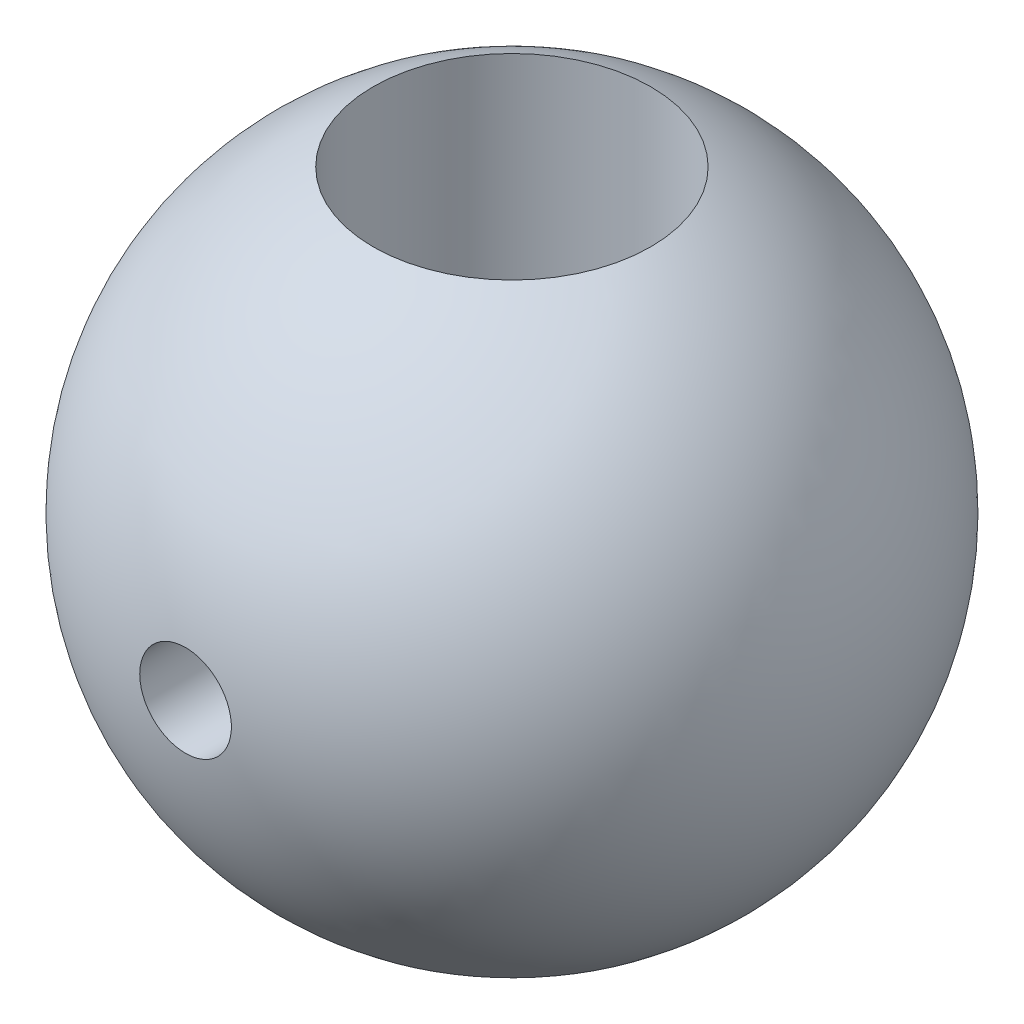
SolidWorks part; units mm, degrees
material "1.4028 (X30Cr13)"
ref_plane "Alzado" through (0, 0, 0) normal (0, 0, 1) x (1, 0, 0)
ref_plane "Planta" through (0, 0, 0) normal (0, 1, 0) x (1, 0, 0)
ref_plane "Vista lateral" through (0, 0, 0) normal (1, 0, 0) x (0, 0, -1)
sketch "Croquis1" plane through (0, 0, 0) normal (0, 0, 1) x (1, 0, 0)
  line L0 (0, -9.5) -> (0, 9.5)
  arc A1 (0, 9.5) -> (0, -9.5) centre (0, 0) cw
  point P2 (0, 0)
  point P4 (0, 0)
  point P5 (0, 0)
  point P8 (0, 0)
  point P9 (0, 0)
  point P10 (0, 0)
  dimension "D1" = 19
revolve "Revolución1" add sketch "Croquis1" angle 360 about L0
sketch "Croquis2" plane through (0, 0, 0) normal (0, 1, 0) x (1, 0, 0)
  circle A0 centre (0, 0) radius 4
  dimension "D1" = 8
extrude "Cortar-Extruir1" cut sketch "Croquis2" against normal blind 10 and the other way through all
hole_wizard "Diámetro de taladro #37 (0.104)1" positions "Croquis3" profile "Croquis4" hole size "#37" standard "Progressive"
sketch "Croquis3" plane through (0, 0, 0) normal (0, 0, 1) x (1, 0, 0)
  point P0 (0, 0)
sketch "Croquis4" plane through (0, 0, 0) normal (1, 0, 0) x (0, 1, 0)
  line L0 (0, 0) -> (0, 9.5)
  line L1 (0, 9.5) -> (1.3208, 9.5)
  line L2 (1.3208, 9.5) -> (1.3208, 0)
  line L5 (1.3208, 0) -> (0, 0)
  line L11 (0, -6.35) -> (0, 107.95) construction
  dimension "Diámetro de taladro hasta el siguiente" = 2.6416
  dimension "Profundidad de taladro hasta el siguiente" = 9.5
